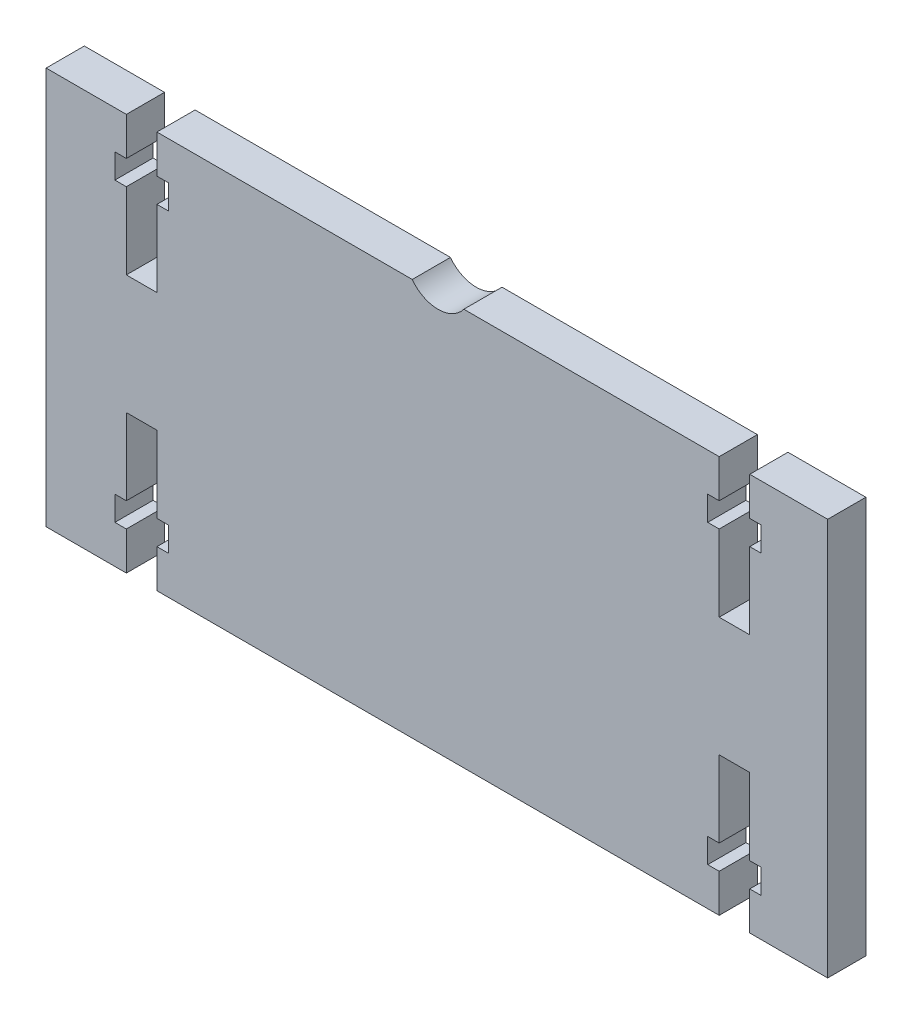
SolidWorks part; units mm, degrees
ref_plane "Front Plane" through (0, 0, 0) normal (0, 0, 1) x (1, 0, 0)
ref_plane "Top Plane" through (0, 0, 0) normal (0, 1, 0) x (1, 0, 0)
ref_plane "Right Plane" through (0, 0, 0) normal (1, 0, 0) x (0, 0, -1)
sketch "Sketch1" plane through (0, 0, 0) normal (0, 0, 1) x (1, 0, 0)
  line L1 (-51.15, 26) -> (51.15, 26)
  line L2 (-51.15, 26) -> (-51.15, -26)
  line L3 (-51.15, -26) -> (51.15, -26)
  line L4 (51.15, 26) -> (51.15, -26)
  dimension "D1" = 102.3
  dimension "D2" = 51.15
  dimension "D3" = 52
  dimension "D4" = 26
extrude "Boss-Extrude1" add sketch "Sketch1" along normal blind 5
sketch "Sketch3" plane through (0, 0, 5) normal (0, 0, 1) x (1, 0, 0)
  line L0 (-38.65, 1.3) -> (-38.65, 16.1452) construction
  line L1 (-36.65, 17.8) -> (-36.65, 7.8)
  line L2 (-40.65, 21) -> (-40.65, 26)
  line L3 (-35.15, 21) -> (-36.65, 21)
  line L4 (-35.15, 17.8) -> (-35.15, 21)
  line L5 (-36.65, 17.8) -> (-35.15, 17.8)
  line L6 (-42.15, 21) -> (-40.65, 21)
  line L7 (-42.15, 17.8) -> (-42.15, 21)
  line L8 (-40.65, 17.8) -> (-42.15, 17.8)
  line L9 (-40.65, 7.8) -> (-36.65, 7.8)
  line L10 (-36.65, 26) -> (-36.65, 21)
  line L11 (-40.65, 26) -> (-36.65, 26)
  line L12 (-40.65, 7.8) -> (-40.65, 17.8)
  line L14 (51.15, 26) -> (-51.15, 26) construction
  line L15 (-51.15, 26) -> (-51.15, -26) construction
  line L16 (0, 26) -> (0, -11.575) construction
  line L17 (51.15, 26) -> (-51.15, 26) construction
  line L18 (0, 0) -> (31.3946, 0) construction
  line L45 (-38.65, -1.3) -> (-38.65, -16.1452) construction
  line L46 (-40.65, -7.8) -> (-40.65, -17.8)
  line L47 (-40.65, -26) -> (-36.65, -26)
  line L48 (-36.65, -26) -> (-36.65, -21)
  line L49 (-40.65, -7.8) -> (-36.65, -7.8)
  line L50 (-40.65, -17.8) -> (-42.15, -17.8)
  line L51 (-42.15, -17.8) -> (-42.15, -21)
  line L52 (-42.15, -21) -> (-40.65, -21)
  line L53 (-36.65, -17.8) -> (-35.15, -17.8)
  line L54 (-35.15, -17.8) -> (-35.15, -21)
  line L55 (-35.15, -21) -> (-36.65, -21)
  line L56 (-40.65, -21) -> (-40.65, -26)
  line L57 (-36.65, -17.8) -> (-36.65, -7.8)
  dimension "D1" = 5
  dimension "D2" = 3.2
  dimension "10" = 10
  dimension "D4" = 2
  dimension "D5" = 4
  dimension "D6" = 1.5
  dimension "D7" = 1.5
  dimension "D8" = 10.5
extrude "Cut-Extrude1" cut sketch "Sketch3" against normal blind 5
sketch "Sketch7" plane through (0, 0, 5) normal (0, 0, 1) x (1, 0, 0)
  line L0 (38.95, 26) -> (38.95, -12.7494) construction
  line L1 (51.15, 26) -> (-36.65, 26) construction
  line L2 (51.15, -26) -> (51.15, 26) construction
  dimension "D1" = 12.2
sketch "Sketch8" plane through (0, 0, 5) normal (0, 0, 1) x (1, 0, 0)
  line L0 (36.95, 26) -> (36.95, 21)
  line L1 (51.15, 26) -> (-36.65, 26) construction
  line L2 (36.95, 21) -> (35.45, 21)
  line L3 (35.45, 21) -> (35.45, 17.8)
  line L4 (35.45, 17.8) -> (36.95, 17.8)
  line L5 (42.45, 17.8) -> (42.45, 21)
  line L6 (42.45, 21) -> (40.95, 21)
  line L7 (40.95, 21) -> (40.95, 26)
  line L8 (36.95, 17.8) -> (36.95, 7.8)
  line L9 (36.95, 7.8) -> (40.95, 7.8)
  line L10 (40.95, 7.8) -> (40.95, 17.8)
  line L11 (40.95, 17.8) -> (42.45, 17.8)
  line L12 (38.95, 26) -> (38.95, -12.7494) construction
  line L14 (0, 0) -> (55.7157, 0) construction
  line L15 (40.95, -17.8) -> (42.45, -17.8)
  line L16 (40.95, -7.8) -> (40.95, -17.8)
  line L17 (36.95, -7.8) -> (40.95, -7.8)
  line L18 (36.95, -17.8) -> (36.95, -7.8)
  line L19 (40.95, -21) -> (40.95, -26)
  line L20 (42.45, -21) -> (40.95, -21)
  line L21 (42.45, -17.8) -> (42.45, -21)
  line L22 (35.45, -17.8) -> (36.95, -17.8)
  line L23 (35.45, -21) -> (35.45, -17.8)
  line L24 (36.95, -21) -> (35.45, -21)
  line L25 (36.95, -26) -> (36.95, -21)
  line L26 (36.95, 26) -> (40.95, 26)
  line L27 (36.95, -26) -> (40.95, -26)
  dimension "D1" = 3.2
  dimension "D2" = 2
  dimension "D3" = 2
  dimension "D4" = 1.5
  dimension "D5" = 1.5
  dimension "D6" = 5
  dimension "D7" = 10
extrude "Cut-Extrude2" cut sketch "Sketch8" against normal blind 10
sketch "Sketch9" plane through (0, 0, 5) normal (0, 0, 1) x (1, 0, 0)
  circle A0 centre (0.15, 28.5) radius 4.2
  point P3 (0, 0)
  dimension "D1" = 8.4
extrude "Cut-Extrude3" cut sketch "Sketch9" against normal blind 5
